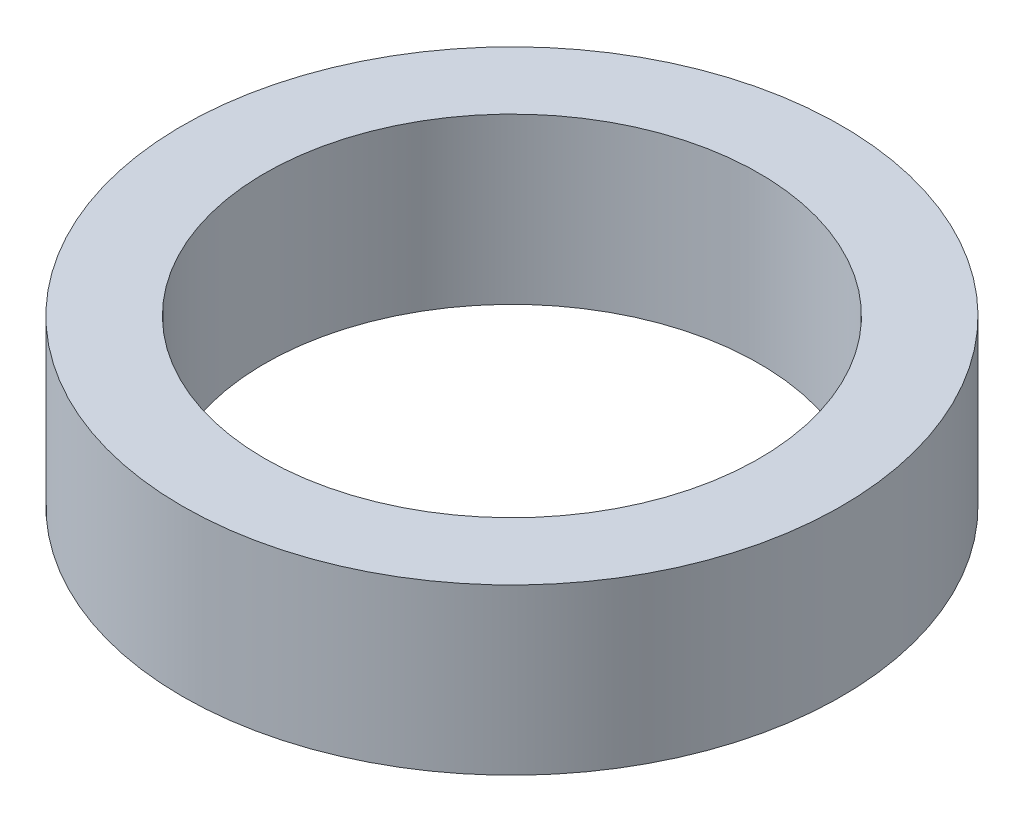
SolidWorks part; units mm, degrees
material "AISI 304"
ref_plane "前视基准面" through (0, 0, 0) normal (0, 0, 1) x (1, 0, 0)
ref_plane "上视基准面" through (0, 0, 0) normal (0, 1, 0) x (1, 0, 0)
ref_plane "右视基准面" through (0, 0, 0) normal (1, 0, 0) x (0, 0, -1)
sketch "Sketch1" plane through (0, 0, 0) normal (0, 1, 0) x (1, 0, 0)
  circle A0 centre (0, 0) radius 15
  circle A1 centre (0, 0) radius 20
  dimension "D1" = 30
  dimension "D2" = 40
extrude "Boss-Extrude1" add sketch "Sketch1" along normal mid plane 10
